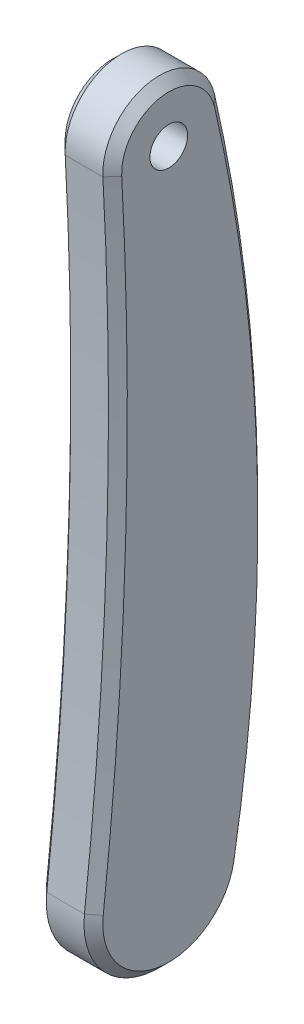
SolidWorks part; units mm, degrees
ref_plane "Front Plane" through (0, 0, 0) normal (1, 0, 0) x (0, 1, 0)
ref_plane "Top Plane" through (0, 0, 0) normal (0, 0, 1) x (0, 1, 0)
ref_plane "Right Plane" through (0, 0, 0) normal (0, 1, 0) x (-1, 0, 0)
sketch "Sketch1" plane through (0, 0, 0) normal (1, 0, 0) x (0, 1, 0)
  line L0 (-85, 0) -> (85, 0) construction
  arc A0 (-82.7465, 19.8726) -> (-88.3618, -19.7154) centre (-85, 0) ccw
  arc A1 (88.3697, -14.6166) -> (84.1861, 14.9779) centre (85, 0) ccw
  arc A2 (-82.7465, 19.8726) -> (84.1861, 14.9779) centre (29.9265, 1013.5048) ccw
  arc A3 (-88.3618, -19.7154) -> (88.3697, -14.6166) centre (-12.7206, 423.8817) ccw
  point P4 (0, 0)
  dimension "D2" = 30
  dimension "D3" = 40
  dimension "D4" = 450
  dimension "D5" = 1000
  dimension "D1" = 170
extrude "Boss-Extrude1" add sketch "Sketch1" along normal mid plane 15
chamfer "Chamfer1" distance 2.5 angle 45 8 edges at (-7.5, 0.2568, -25.9311) (-7.5, 99.8523, 2.0996) (-7.5, -104.8018, 2.8087) (-7.5, 0.6174, 13.9344) (7.5, 0.2568, -25.9311) (7.5, 99.8523, 2.0996) (7.5, -104.8018, 2.8087) (7.5, 0.6174, 13.9344)
sketch "Sketch2" plane through (-7.5, 0, 0) normal (-1, 0, 0) x (0, -1, 0)
  circle A0 centre (85, 0) radius 5
extrude "Boss-Extrude2" add sketch "Sketch2" along normal blind 10
sketch "Sketch3" plane through (7.5, 0, 0) normal (1, 0, 0) x (0, 1, 0)
  circle A0 centre (85, 0) radius 5
extrude "Cut-Extrude1" cut sketch "Sketch3" against normal blind 10
